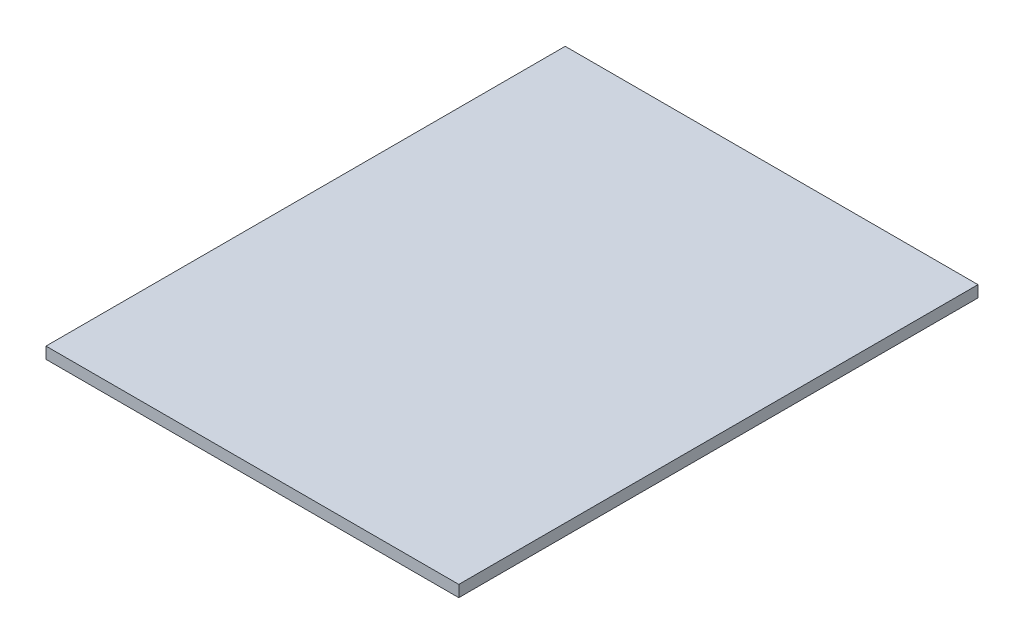
SolidWorks part; units mm, degrees
ref_plane "Front Plane" through (0, 0, 0) normal (0, 0, 1) x (1, 0, 0)
ref_plane "Top Plane" through (0, 0, 0) normal (0, 1, 0) x (1, 0, 0)
ref_plane "Right Plane" through (0, 0, 0) normal (1, 0, 0) x (0, 0, -1)
sketch "Sketch1" plane through (0, 0, 0) normal (0, 1, 0) x (1, 0, 0)
  line L1 (-305, 55.73) -> (304, 55.73)
  line L2 (-305, 55.73) -> (-305, -710.27)
  line L3 (-305, -710.27) -> (304, -710.27)
  line L4 (304, 55.73) -> (304, -710.27)
  dimension "D1" = 609
  dimension "D2" = 766
  dimension "D3" = 55.73
  dimension "D4" = 305
extrude "Boss-Extrude1" add sketch "Sketch1" along normal blind 17
